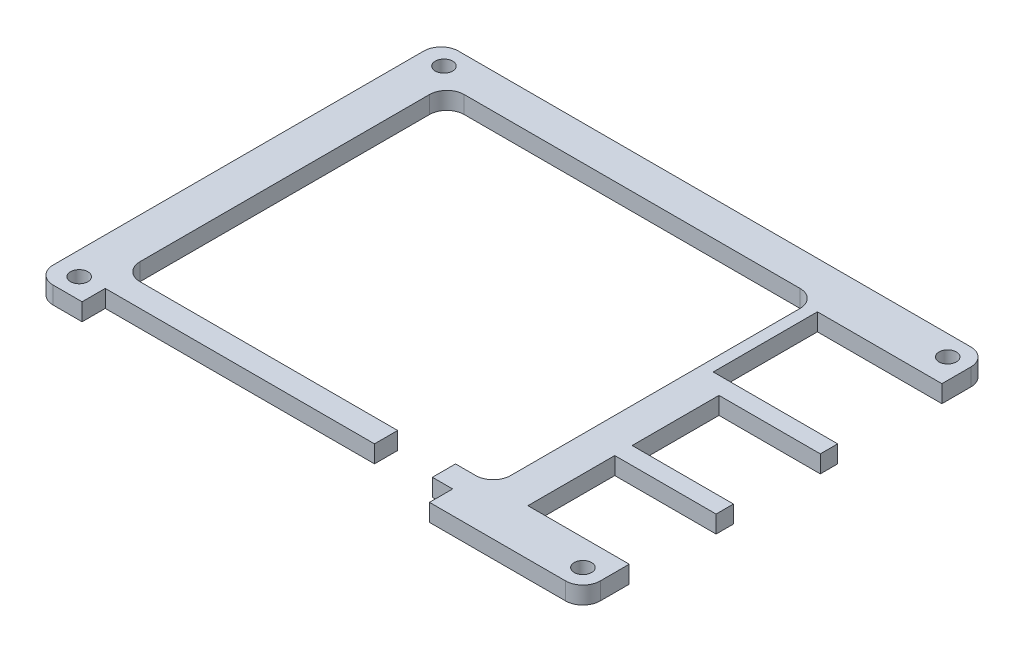
SolidWorks part; units mm, degrees
material "ABS"
ref_plane "Front Plane" through (0, 0, 0) normal (0, 0, 1) x (1, 0, 0)
ref_plane "Top Plane" through (0, 0, 0) normal (0, 1, 0) x (1, 0, 0)
ref_plane "Right Plane" through (0, 0, 0) normal (1, 0, 0) x (0, 0, -1)
sketch "Sketch1" plane through (0, 0, 0) normal (0, 1, 0) x (1, 0, 0)
  line L1 (-47.25, 35) -> (47.25, 35)
  line L2 (-47.25, 35) -> (-47.25, -35)
  line L3 (-47.25, -35) -> (47.25, -35)
  line L4 (47.25, 35) -> (47.25, -35)
  line L5 (-47.25, 35) -> (47.25, -35) construction
  line L6 (-47.25, -35) -> (47.25, 35) construction
  point P0 (0, 0)
  dimension "D1" = 70
  dimension "D2" = 94.5
extrude "Boss-Extrude1" add sketch "Sketch1" along normal blind 3
sketch "Sketch3" plane through (0, 3, 0) normal (0, 1, 0) x (1, 0, 0)
  line L0 (47.25, -35) -> (47.25, 35) construction
  line L2 (47.25, 35) -> (-47.25, 35) construction
  circle A0 centre (43.75, 31.5) radius 1.5
  circle A1 centre (-43.25, 31.5) radius 1.5
  circle A2 centre (-43.25, -31.5) radius 1.5
  circle A3 centre (43.75, -31.5) radius 1.5
  dimension "D1" = 3
  dimension "D2" = 3.5
  dimension "D3" = 3.5
  dimension "D4" = 2
  dimension "D5" = 87
  dimension "D6" = 63
  dimension "D7" = 2
extrude "Cut-Extrude2" cut sketch "Sketch3" against normal through all
fillet "Fillet2" radius 3 4 edges at (-47.25, 1.5, 35) (-47.25, 1.5, -35) (47.25, 1.5, -35) (47.25, 1.5, 35)
sketch "Sketch5" plane through (0, 3, 0) normal (0, 1, 0) x (1, 0, 0)
  line L0 (-40.25, 29) -> (23.75, 29)
  line L1 (23.75, 29) -> (23.75, -27)
  line L2 (23.75, -27) -> (-40.25, -27)
  line L3 (-40.25, -27) -> (-40.25, 29)
  line L4 (47.25, 27) -> (25.75, 27)
  line L5 (47.25, -32) -> (47.25, 32) construction
  line L6 (25.75, 27) -> (25.75, 9)
  line L7 (25.75, 9) -> (47.25, 9)
  line L8 (47.25, 9) -> (47.25, 27)
  line L9 (47.25, 6) -> (29.75, 6)
  line L10 (29.75, 6) -> (29.75, -9)
  line L11 (29.75, -9) -> (47.25, -9)
  line L12 (47.25, -9) -> (47.25, 6)
  line L13 (47.25, -12) -> (29.75, -12)
  line L14 (29.75, -12) -> (29.75, -27)
  line L15 (29.75, -27) -> (47.25, -27)
  line L16 (47.25, -27) -> (47.25, -12)
  line L17 (44.25, 35) -> (-44.25, 35) construction
  line L18 (-47.25, 32) -> (-47.25, -32) construction
  line L19 (7.25, -27) -> (7.25, -31)
  line L20 (7.25, -31) -> (-39.25, -31)
  line L21 (-39.25, -31) -> (-39.25, -35)
  line L22 (-44.25, -35) -> (44.25, -35) construction
  line L23 (-39.25, -35) -> (20.75, -35)
  line L24 (20.75, -35) -> (20.75, -31)
  line L25 (20.75, -31) -> (17.25, -31)
  line L26 (17.25, -31) -> (17.25, -27)
  line M19 (-44.25, -35) -> (44.25, -35)
  line M21 (47.25, -32) -> (47.25, 32)
  dimension "D1" = 6
  dimension "D2" = 7
  dimension "D3" = 64
  dimension "D4" = 56
  dimension "D5" = 18
  dimension "D6" = 2
  dimension "D7" = 6
  dimension "D8" = 3
  dimension "D9" = 8
  dimension "D10" = 15
  dimension "D11" = 3
  dimension "D12" = 15
  dimension "D13" = 6
  dimension "D14" = 60
  dimension "D15" = 8
  dimension "D16" = 10
  dimension "D17" = 4
  dimension "D18" = 54.5
extrude "Cut-Extrude3" cut sketch "Sketch5" against normal through all contours L3 L2 L1 L0 | L6 L7 L4 M21 | L10 L11 L9 M21 | L14 L15 L13 M21 | L25 L26 L2 L19 L20 L21 L24 M19
fillet "Fillet3" radius 3 4 edges at (23.75, 1.5, -29) (23.75, 1.5, 27) (-40.25, 1.5, 27) (-40.25, 1.5, -29)
